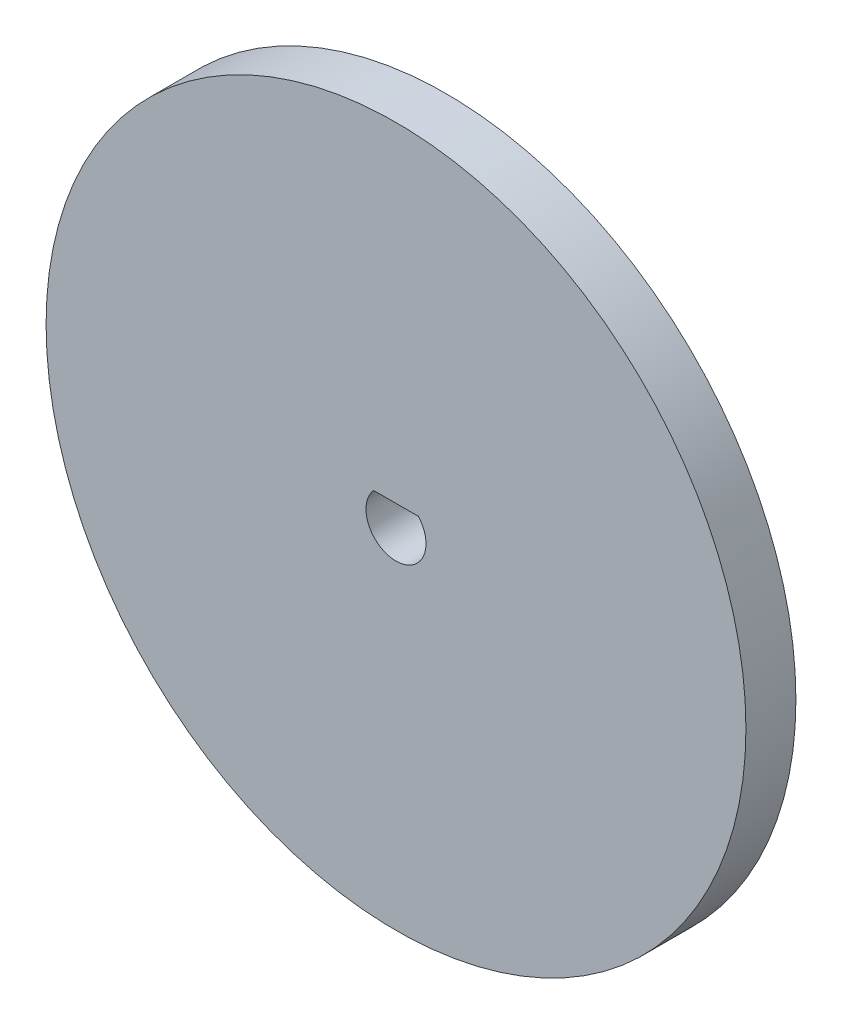
SolidWorks part; units mm, degrees
ref_plane "Plano frontal" through (0, 0, 0) normal (0, 0, 1) x (1, 0, 0)
ref_plane "Plano superior" through (0, 0, 0) normal (0, 1, 0) x (1, 0, 0)
ref_plane "Plano direito" through (0, 0, 0) normal (1, 0, 0) x (0, 0, -1)
sketch "Esboço1" plane through (0, 0, 0) normal (0, 0, 1) x (1, 0, 0)
  line L0 (-1.12, 0.9978) -> (1.12, 0.9978)
  arc A0 (-1.12, 0.9978) -> (1.12, 0.9978) centre (0, 0) ccw
  circle A1 centre (0, 0) radius 17.5
  dimension "D1" = 2.24
  dimension "D2" = 3
  dimension "D3" = 35
extrude "Ressalto-extrusão1" add sketch "Esboço1" along normal blind 2.5
